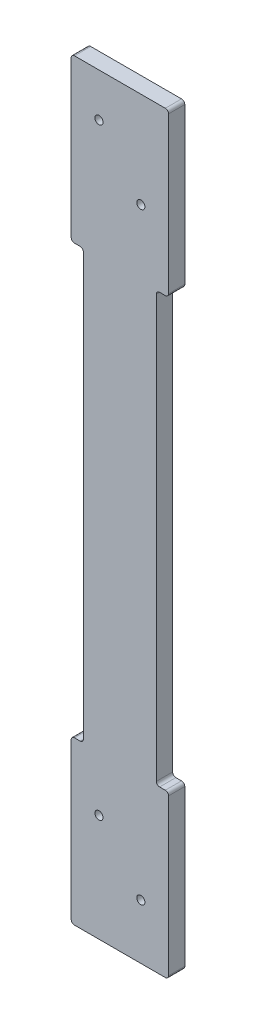
SolidWorks part; units mm, degrees
ref_plane "Front Plane" through (0, 0, 0) normal (0, 0, 1) x (1, 0, 0)
ref_plane "Top Plane" through (0, 0, 0) normal (0, 1, 0) x (1, 0, 0)
ref_plane "Right Plane" through (0, 0, 0) normal (1, 0, 0) x (0, 0, -1)
sketch "Sketch1" plane through (0, 0, 0) normal (0, 0, 1) x (1, 0, 0)
  line L0 (25, 42.8571) -> (85, 42.8571)
  line L2 (25, 42.8571) -> (25, -57.1429)
  line L3 (25, -57.1429) -> (85, -57.1429)
  line L4 (85, 42.8571) -> (85, -57.1429)
  line L5 (32.5, 42.8571) -> (85, -57.1429) construction
  line L6 (25, -57.1429) -> (77.5, 42.8571) construction
  line L7 (55, 0) -> (55, -408.4443) construction
  line L8 (32.5, -321.2007) -> (32.5, -57.1429)
  line L9 (25, -421.2007) -> (85, -421.2007)
  line L10 (25, -421.2007) -> (25, -321.2007)
  line L11 (25, -321.2007) -> (85, -321.2007)
  line L12 (85, -421.2007) -> (85, -321.2007)
  line L13 (25, -421.2007) -> (85, -321.2007) construction
  line L14 (25, -321.2007) -> (85, -421.2007) construction
  line L15 (77.5, -321.2007) -> (77.5, -57.1429)
  circle A1 centre (67.9051, -16.1417) radius 2.5 construction
  circle A2 centre (42.0949, 16.1417) radius 2.5 construction
  circle A3 centre (67.9051, -16.1417) radius 2.5
  circle A4 centre (42.0949, 16.1417) radius 2.5
  circle A5 centre (42.0949, -355.059) radius 2.5
  circle A6 centre (67.9051, -387.3423) radius 2.5
  point P0 (55, 0)
  point P10 (55, -371.2007)
  dimension "D1" = 100
  dimension "D2" = 60
  dimension "D3" = 100
  dimension "D4" = 60
  dimension "D5" = 30
  dimension "D6" = 45
extrude "Boss-Extrude1" add sketch "Sketch1" along normal blind 10
fillet "Fillet1" radius 2 12 edges at (85, -421.2007, 5) (85, -321.2007, 5) (77.5, -321.2007, 5) (32.5, -321.2007, 5) (25, -321.2007, 5) (25, -421.2007, 5) (77.5, -57.1429, 5) (85, -57.1429, 5) (85, 42.8571, 5) (25, 42.8571, 5) (25, -57.1429, 5) (32.5, -57.1429, 5)
